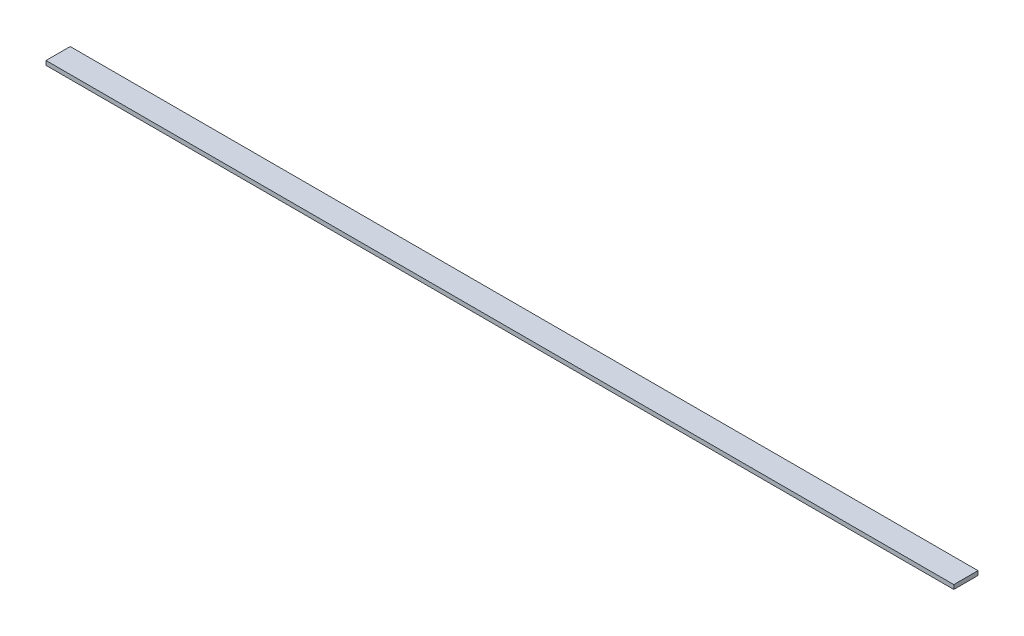
SolidWorks part; units mm, degrees
ref_plane "Vorne" through (0, 0, 0) normal (0, 0, 1) x (1, 0, 0)
ref_plane "Oben" through (0, 0, 0) normal (0, 1, 0) x (1, 0, 0)
ref_plane "Rechts" through (0, 0, 0) normal (1, 0, 0) x (0, 0, -1)
ref_plane "E_Boden" through (0, 1, 0) normal (0, 1, 0) x (1, 0, 0)
sketch "Skizze1" plane through (0, 0, 0) normal (0, 1, 0) x (1, 0, 0)
  line L0 (0, 0) -> (-118.8274, 0) construction
  line L1 (-118.8274, 0) -> (167.8176, 0) construction
  line L2 (0, 0) -> (0, 71.7915) construction
  line L3 (0, 71.7915) -> (0, -82.215) construction
  line L5 (-750, 20) -> (750, 20)
  line L6 (-750, 20) -> (-750, -20)
  line L7 (-750, -20) -> (750, -20)
  line L8 (750, 20) -> (750, -20)
  dimension "D1" = 40
  dimension "D2" = 1500
extrude "Aufsatz-Linear austragen1" add sketch "Skizze1" along normal blind 7
